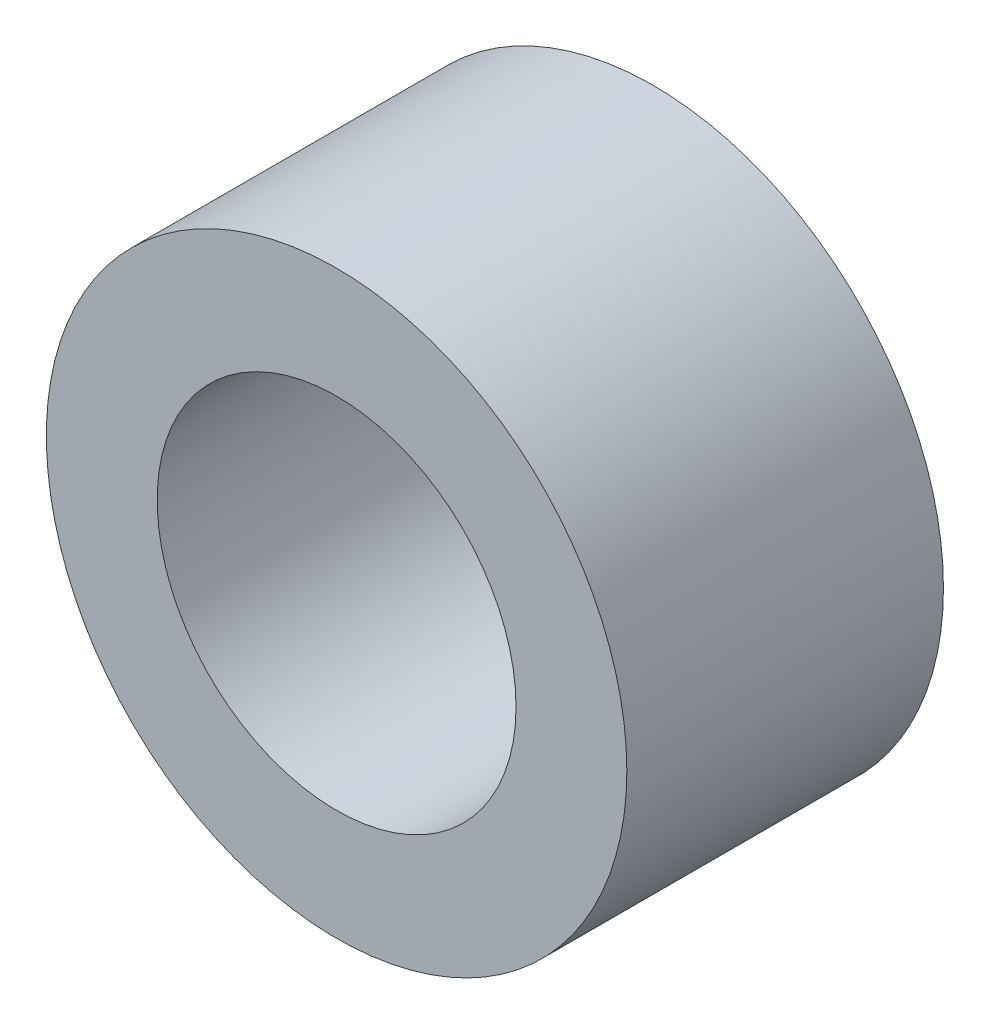
SolidWorks part; units mm, degrees
material "ABS"
ref_plane "前视基准面" through (0, 0, 0) normal (0, 0, 1) x (1, 0, 0)
ref_plane "上视基准面" through (0, 0, 0) normal (0, 1, 0) x (1, 0, 0)
ref_plane "右视基准面" through (0, 0, 0) normal (1, 0, 0) x (0, 0, -1)
sketch "草图1" plane through (0, 0, 0) normal (0, 0, 1) x (1, 0, 0)
  circle A0 centre (0, 0) radius 1.7
  circle A1 centre (0, 0) radius 2.75
  dimension "D1" = 5.5
  dimension "D2" = 3.4
extrude "凸台-拉伸1" add sketch "草图1" along normal blind 3
